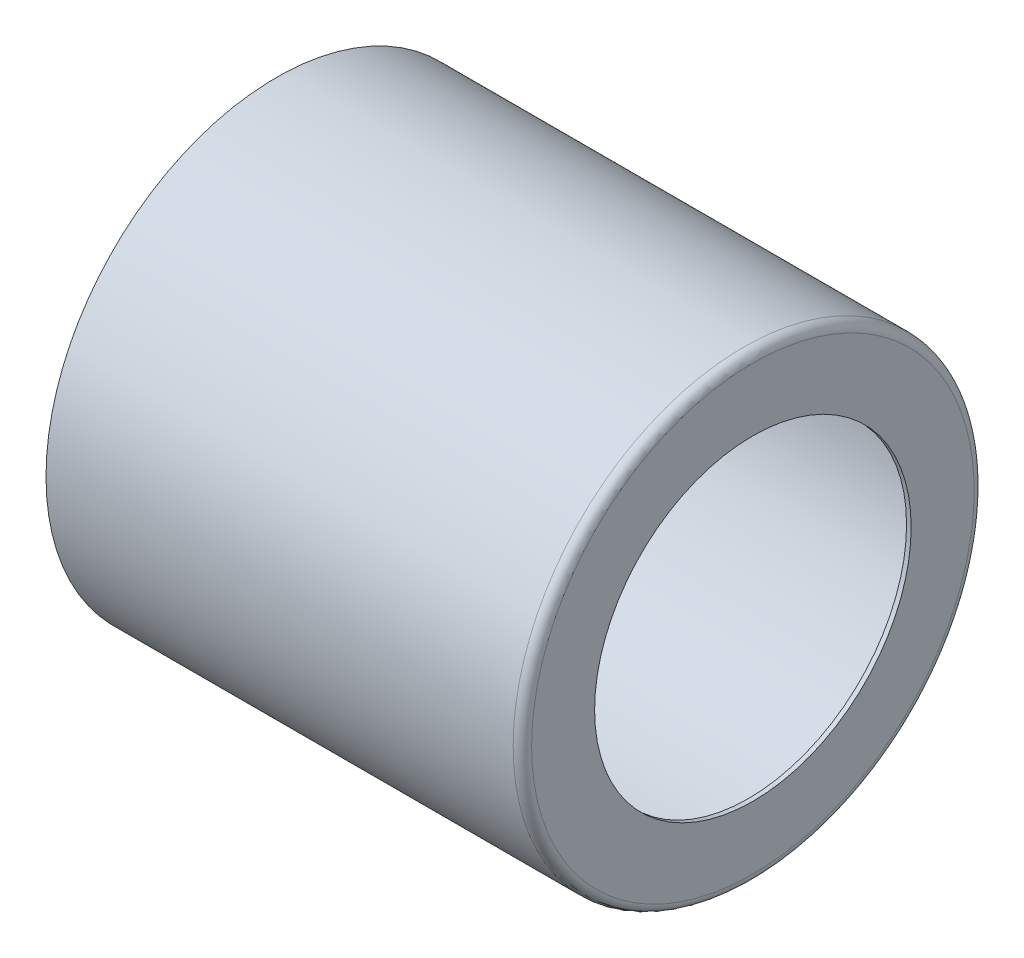
SolidWorks part; units mm, degrees
material "AISI 316 Stainless Steel Sheet (SS)"
ref_plane "Front Plane" through (0, 0, 0) normal (0, 0, 1) x (1, 0, 0)
ref_plane "Top Plane" through (0, 0, 0) normal (0, 1, 0) x (1, 0, 0)
ref_plane "Right Plane" through (0, 0, 0) normal (1, 0, 0) x (0, 0, -1)
sketch "Sketch1" plane through (0, 0, 0) normal (0, 0, 1) x (1, 0, 0)
  line L0 (-120.0179, 0) -> (5880.8787, 0) construction
  line L2 (0, 75) -> (152, 75)
  line L3 (0, 75) -> (0, 73.5)
  line L4 (0, 73.5) -> (150.5, 73.5)
  line L7 (153.5, 70.5) -> (153.5, 51.5)
  line L8 (153.5, 51.5) -> (155, 51.5)
  line L9 (155, 72) -> (155, 51.5)
  arc A0 (150.5, 73.5) -> (153.5, 70.5) centre (150.5, 70.5) cw
  arc A1 (155, 72) -> (152, 75) centre (152, 72) ccw
  dimension "D6" = 3
  dimension "D4" = 3
  dimension "D1" = 1.5
  dimension "D2" = 1.5
  dimension "D3" = 75
  dimension "D5" = 51.5
  dimension "D7" = 152
revolve "Revolve1" add sketch "Sketch1" angle 360 about L0
